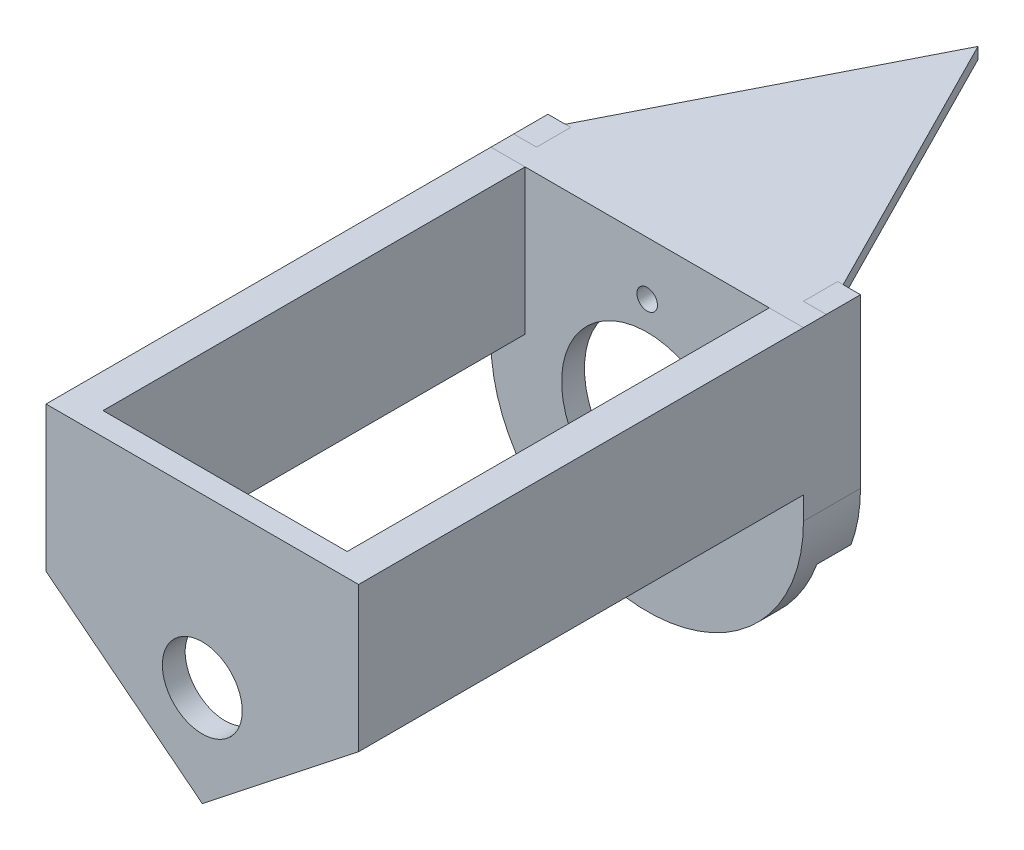
SolidWorks part; units mm, degrees
ref_plane "Front" through (0, 0, 0) normal (0, 0, 1) x (1, 0, 0)
ref_plane "Top" through (0, 0, 0) normal (0, 1, 0) x (1, 0, 0)
ref_plane "Right" through (0, 0, 0) normal (1, 0, 0) x (0, 0, -1)
sketch "Sketch2" plane through (0, 0, 0) normal (0, 0, 1) x (1, 0, 0)
  line L0 (0, 0) -> (0, 13.7) construction
  line L2 (-13.7, 13.7) -> (13.7, 13.7)
  line L3 (-13.7, 13.7) -> (-13.7, 0)
  line L4 (-13.7, 0) -> (13.7, 0)
  line L5 (13.7, 13.7) -> (13.7, 0)
  line L6 (-13.7, 13.7) -> (13.7, 0) construction
  line L7 (-13.7, 0) -> (13.7, 13.7) construction
  circle A0 centre (0, 0) radius 13.7
  point P3 (0, 6.85)
  point P5 (0, 6.85)
  dimension "D1" = 27.4
extrude "Boss-Extrude1" add sketch "Sketch2" along normal blind 2 contours L4 A0 | A0 L5 L2 | A0 L2 L3 | L4 A0
sketch "Sketch3" plane through (0, 0, 0) normal (0, 0, -1) x (-1, 0, 0)
  line L0 (-12.8738, 4.6857) -> (12.8738, -4.6857)
  line L1 (-12.8738, -4.6857) -> (12.8738, 4.6857)
  line L2 (-13.7, 0) -> (13.7, 0) construction
  line L3 (13.7, 0) -> (13.7, 13.7)
  line L4 (13.7, 13.7) -> (-13.7, 13.7)
  line L5 (-13.7, 13.7) -> (-13.7, 0)
  line L6 (13.7, 0) -> (13.7, 13.7)
  line L7 (13.7, 13.7) -> (-13.7, 13.7)
  line L8 (-13.7, 13.7) -> (-13.7, 0)
  circle A0 centre (0, 0) radius 13.7
  arc A1 (-13.7, 0) -> (13.7, 0) centre (0, 0) ccw
  arc A2 (-13.7, 0) -> (13.7, 0) centre (0, 0) ccw
  circle A3 centre (0, 0) radius 11.7
  arc M5 (-13.7, 0) -> (13.7, 0) centre (0, 0) ccw
  dimension "D4" = 2
  dimension "D2" = 20
  dimension "D3" = 40
  dimension "D1" = 0
extrude "Boss-Extrude2" add sketch "Sketch3" along normal blind 3 contours L2 L1 A3 M5 | L2 A3 L0 M5
sketch "Sketch5" plane through (0, 0, 2) normal (0, 0, 1) x (1, 0, 0)
  circle A0 centre (0, 0) radius 7.5
  dimension "D1" = 15
extrude "Cut-Extrude1" cut sketch "Sketch5" against normal up to next
sketch "Sketch7" plane through (0, 13.7, 0) normal (0, 1, 0) x (1, 0, 0)
  line L0 (0, -1.6254) -> (0, 4.5247) construction
  line L1 (13.7, 0) -> (0, 27)
  line L2 (0, 27) -> (-13.7, 0)
  line L4 (13.7, 0) -> (-13.7, 0)
  line L5 (-13.7, 0) -> (-13.7, -2)
  line L6 (-13.7, -2) -> (13.7, -2)
  line L7 (13.7, -2) -> (13.7, 0)
  line L8 (13.7, 0) -> (-13.7, 0)
  line L9 (-13.7, 0) -> (-13.7, -2)
  line L10 (-13.7, -2) -> (13.7, -2)
  line L11 (13.7, -2) -> (13.7, 0)
  point P5 (0, 27)
  line M5 (13.7, 0) -> (-13.7, 0)
  line M6 (-13.7, 0) -> (-13.7, -2)
  line M7 (-13.7, -2) -> (13.7, -2)
  line M8 (13.7, -2) -> (13.7, 0)
  dimension "D2" = 27
  dimension "D1" = 0
extrude "Boss-Extrude3" add sketch "Sketch7" along normal blind 1 contours L8 L0 L2 | L0 L1 M5 | L0 L8 M7 M6 | L0 L10 M8 M5
sketch "Sketch8" plane through (0, 0, 2) normal (0, 0, 1) x (1, 0, 0)
  line L0 (-10.7, 2) -> (-13.7, 2)
  line L1 (-13.7, 0) -> (-10.7, 0)
  line L2 (-13.7, 0) -> (-13.7, 7)
  line L3 (13.7, 0) -> (13.7, 14.7)
  line L4 (13.7, 14.7) -> (-13.7, 14.7)
  line L5 (-13.7, 14.7) -> (-13.7, 0)
  line L6 (13.7, 0) -> (13.7, 14.7)
  line L7 (13.7, 14.7) -> (-13.7, 14.7)
  line L8 (-13.7, 14.7) -> (-13.7, 0)
  line L9 (-13.7, 7) -> (-10.7, 7)
  line L10 (-10.7, 0) -> (-10.7, 7)
  line L11 (13.7, 0) -> (10.7, 0)
  line L12 (13.7, 0) -> (13.7, 7)
  line L13 (13.7, 7) -> (10.7, 7)
  line L14 (10.7, 0) -> (10.7, 7)
  line L15 (13.7, 2) -> (10.7, 2)
  arc A1 (-13.7, 0) -> (13.7, 0) centre (0, 0) ccw
  arc A2 (-13.7, 0) -> (13.7, 0) centre (0, 0) ccw
  line M7 (13.7, 0) -> (13.7, 14.7)
  line M9 (-13.7, 14.7) -> (-13.7, 0)
  dimension "D2" = 7
  dimension "D3" = 3
  dimension "D4" = 7
  dimension "D5" = 3
  dimension "D6" = 5
  dimension "D7" = 5
  dimension "D1" = 0
extrude "Boss-Extrude4" add sketch "Sketch8" along normal blind 39 contours L1 L10 L9 M9 | L14 L11 L13 M7
sketch "Sketch9" plane through (0, 0, 41) normal (0, 0, 1) x (1, 0, 0)
  line L0 (-13.7, 2) -> (-10.7, 2) construction
  line L1 (-10.7, 2) -> (-10.7, 7) construction
  line L2 (-10.7, 7) -> (-13.7, 7) construction
  line L3 (-13.7, 7) -> (-13.7, 2) construction
  line L4 (10.7, 2) -> (13.7, 2) construction
  line L5 (13.7, 2) -> (13.7, 7) construction
  line L6 (13.7, 7) -> (10.7, 7) construction
  line L7 (10.7, 7) -> (10.7, 2) construction
  line L8 (-13.7, 2) -> (-10.7, 2)
  line L9 (-10.7, 2) -> (-10.7, 7)
  line L10 (-10.7, 7) -> (-13.7, 7)
  line L11 (-13.7, 7) -> (-13.7, 2)
  line L12 (10.7, 2) -> (13.7, 2)
  line L13 (13.7, 2) -> (13.7, 7)
  line L14 (13.7, 7) -> (10.7, 7)
  line L15 (10.7, 7) -> (10.7, 2)
  line L16 (-10.7, 7) -> (10.7, 7)
  line L17 (-10.7, -8.7864) -> (10.7, -8.7864)
  line L18 (13.7, 2) -> (0, -8.7864)
  line L19 (0, -8.7864) -> (-13.7, 2)
  circle A0 centre (0, 0) radius 13.8452
  line M1 (10.7, 2) -> (13.7, 2)
  line M4 (10.7, 7) -> (10.7, 2)
extrude "Boss-Extrude5" add sketch "Sketch9" against normal blind 2 contours L14 A0 L10 L9 L8 M1 M4
sketch "Sketch10" plane through (0, 0, 41) normal (0, 0, 1) x (1, 0, 0)
  circle A0 centre (0, 0) radius 3.5
  dimension "D1" = 7
extrude "Cut-Extrude2" cut sketch "Sketch10" against normal up to next
sketch "Sketch11" plane through (0, 0, 2) normal (0, 0, 1) x (1, 0, 0)
  line L11 (13.7, 2) -> (10.7, 2)
  line L12 (10.7, 2) -> (10.7, 7)
  line L13 (10.7, 7) -> (13.7, 7)
  line L14 (13.7, 7) -> (13.7, 14.7)
  line L15 (13.7, 14.7) -> (-13.7, 14.7)
  line L16 (-13.7, 14.7) -> (-13.7, 7)
  line L17 (-13.7, 7) -> (-10.7, 7)
  line L18 (-10.7, 7) -> (-10.7, 2)
  line L19 (-10.7, 2) -> (-13.7, 2)
  line L20 (-13.7, 2) -> (-13.7, 0)
  line L21 (13.7, 0) -> (13.7, 2)
  line L22 (13.7, 2) -> (10.7, 2)
  line L23 (10.7, 2) -> (10.7, 7)
  line L24 (10.7, 7) -> (13.7, 7)
  line L28 (-13.7, 7) -> (-10.7, 7)
  line L29 (-10.7, 7) -> (-10.7, 2)
  line L30 (-10.7, 2) -> (-13.7, 2)
  line L31 (-13.7, 2) -> (-13.7, 0)
  line L32 (13.7, 0) -> (13.7, 2)
  circle A0 centre (0, 0) radius 10 construction
  arc A1 (-13.7, 0) -> (13.7, 0) centre (0, 0) ccw
  circle A3 centre (0, 10) radius 0.9
  circle A4 centre (0, -10) radius 0.9
  dimension "D2" = 20
  dimension "D3" = 1.8
  dimension "D4" = 1.8
  dimension "D1" = 0
extrude "Cut-Extrude4" cut sketch "Sketch11" against normal up to next contours A3 | A4
sketch "Sketch15" plane through (0, 7, 0) normal (0, 1, 0) x (1, 0, 0)
  line L8 (-10.7, -2) -> (-13.7, -2)
  line L9 (-13.7, -2) -> (-13.7, -41)
  line L10 (-13.7, -41) -> (13.7, -41)
  line L11 (13.7, -41) -> (13.7, -2)
  line L12 (13.7, -2) -> (10.7, -2)
  line L13 (10.7, -2) -> (10.7, -39)
  line L14 (10.7, -39) -> (-10.7, -39)
  line L15 (-10.7, -39) -> (-10.7, -2)
  line L16 (-10.7, -2) -> (-13.7, -2)
  line L17 (-13.7, -2) -> (-13.7, -41)
  line L18 (-13.7, -41) -> (13.7, -41)
  line L19 (13.7, -41) -> (13.7, -2)
  line L20 (13.7, -2) -> (10.7, -2)
  line L21 (10.7, -2) -> (10.7, -39)
  line L22 (10.7, -39) -> (-10.7, -39)
  line L23 (-10.7, -39) -> (-10.7, -2)
  dimension "D1" = 0
extrude "Boss-Extrude6" add sketch "Sketch15" along normal through all
sketch "Sketch16" plane through (0, 0, 0) normal (0, 1, 0) x (1, 0, 0)
  line L0 (11.7, 0) -> (13.7, 0) construction
  line L1 (13.7, 0) -> (13.7, 3) construction
  line L2 (13.7, 3) -> (11.7, 3) construction
  line L3 (11.7, 3) -> (11.7, 0) construction
  line L4 (-13.7, 0) -> (-11.7, 0) construction
  line L5 (-11.7, 0) -> (-11.7, 3) construction
  line L6 (-11.7, 3) -> (-13.7, 3) construction
  line L7 (-13.7, 3) -> (-13.7, 0) construction
  line L8 (11.7, 0) -> (13.7, 0)
  line L9 (13.7, 0) -> (13.7, 3)
  line L10 (13.7, 3) -> (11.7, 3)
  line L11 (11.7, 3) -> (11.7, 0)
  line L12 (-13.7, 0) -> (-11.7, 0)
  line L13 (-11.7, 0) -> (-11.7, 3)
  line L14 (-11.7, 3) -> (-13.7, 3)
  line L15 (-13.7, 3) -> (-13.7, 0)
extrude "Boss-Extrude7" add sketch "Sketch16" along normal through all
